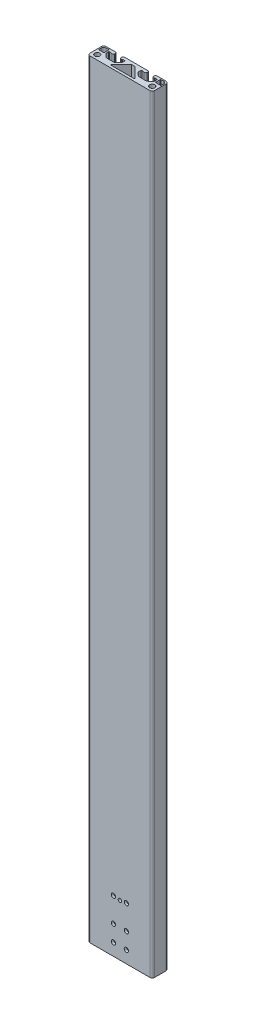
SolidWorks part; units mm, degrees
ref_plane "Front Plane" through (0, 0, 0) normal (0, 0, 1) x (1, 0, 0)
ref_plane "Top Plane" through (0, 0, 0) normal (0, 1, 0) x (1, 0, 0)
ref_plane "Right Plane" through (0, 0, 0) normal (1, 0, 0) x (0, 0, -1)
ref_plane "Plane1" through (0, 0, 0) normal (0, -1, 0) x (1, 0, 0)
sketch "Sketch1" plane through (0, 0, 0) normal (0, -1, 0) x (1, 0, 0)
  line L0 (7.45, -18.5) -> (4.3, -18.5)
  line L1 (1.5, -15.7) -> (1.5, -12.75)
  line L2 (2.25, -12) -> (7.45, -12)
  line L3 (8.2, -12.75) -> (8.2, -17.75)
  line L4 (54.5464, -3.8536) -> (41.9, -16.5)
  line L5 (41.9, -16.5) -> (38.1, -16.5)
  line L6 (38.1, -16.5) -> (25.4536, -3.8536)
  line L7 (25.8071, -3) -> (54.1929, -3)
  line L8 (71.8, -17.75) -> (71.8, -12.75)
  line L9 (72.55, -12) -> (77.75, -12)
  line L10 (78.5, -12.75) -> (78.5, -15.7)
  line L11 (75.7, -18.5) -> (72.55, -18.5)
  line L12 (77, 0) -> (3, 0)
  line L13 (0, -3) -> (0, -17)
  line L14 (3, -20) -> (14.5, -20)
  line L15 (16, -18.5) -> (16, -17.5)
  line L16 (14.5, -16) -> (13.2, -16)
  line L17 (13.2, -16) -> (13.2, -16.5)
  line L18 (13.2, -16.5) -> (10.75, -16.5)
  line L19 (10, -15.75) -> (10, -12.8107)
  line L20 (10.2197, -12.2803) -> (13.1088, -9.3912)
  line L21 (16.4675, -8) -> (23.5325, -8)
  line L22 (26.8912, -9.3912) -> (29.7803, -12.2803)
  line L23 (30, -12.8107) -> (30, -15.75)
  line L24 (29.25, -16.5) -> (26.8, -16.5)
  line L25 (26.8, -16.5) -> (26.8, -16)
  line L26 (26.8, -16) -> (25.5, -16)
  line L27 (24, -17.5) -> (24, -18.5)
  line L28 (25.5, -20) -> (54.5, -20)
  line L29 (56, -18.5) -> (56, -17.5)
  line L30 (54.5, -16) -> (53.2, -16)
  line L31 (53.2, -16) -> (53.2, -16.5)
  line L32 (53.2, -16.5) -> (50.75, -16.5)
  line L33 (50, -15.75) -> (50, -12.8107)
  line L34 (50.2197, -12.2803) -> (53.1088, -9.3912)
  line L35 (56.4675, -8) -> (63.5325, -8)
  line L36 (66.8912, -9.3912) -> (69.7803, -12.2803)
  line L37 (70, -12.8107) -> (70, -15.75)
  line L38 (69.25, -16.5) -> (66.8, -16.5)
  line L39 (66.8, -16.5) -> (66.8, -16)
  line L40 (66.8, -16) -> (65.5, -16)
  line L41 (64, -17.5) -> (64, -18.5)
  line L42 (65.5, -20) -> (77, -20)
  line L43 (80, -17) -> (80, -3)
  circle A0 centre (6, -6) radius 3.175
  arc A1 (8.2, -17.75) -> (7.45, -18.5) centre (7.45, -17.75) cw
  arc A2 (4.3, -18.5) -> (1.5, -15.7) centre (4.3, -15.7) cw
  arc A3 (1.5, -12.75) -> (2.25, -12) centre (2.25, -12.75) cw
  arc A4 (7.45, -12) -> (8.2, -12.75) centre (7.45, -12.75) cw
  arc A5 (25.4536, -3.8536) -> (25.8071, -3) centre (25.8071, -3.5) cw
  arc A6 (54.1929, -3) -> (54.5464, -3.8536) centre (54.1929, -3.5) cw
  circle A7 centre (74, -6) radius 3.175
  arc A8 (72.55, -18.5) -> (71.8, -17.75) centre (72.55, -17.75) cw
  arc A9 (71.8, -12.75) -> (72.55, -12) centre (72.55, -12.75) cw
  arc A10 (77.75, -12) -> (78.5, -12.75) centre (77.75, -12.75) cw
  arc A11 (78.5, -15.7) -> (75.7, -18.5) centre (75.7, -15.7) cw
  arc A12 (80, -3) -> (77, 0) centre (77, -3) ccw
  arc A13 (3, 0) -> (0, -3) centre (3, -3) ccw
  arc A14 (0, -17) -> (3, -20) centre (3, -17) ccw
  arc A15 (14.5, -20) -> (16, -18.5) centre (14.5, -18.5) ccw
  arc A16 (16, -17.5) -> (14.5, -16) centre (14.5, -17.5) ccw
  arc A17 (10.75, -16.5) -> (10, -15.75) centre (10.75, -15.75) cw
  arc A18 (10, -12.8107) -> (10.2197, -12.2803) centre (10.75, -12.8107) cw
  arc A19 (13.1088, -9.3912) -> (16.4675, -8) centre (16.4675, -12.75) cw
  arc A20 (23.5325, -8) -> (26.8912, -9.3912) centre (23.5325, -12.75) cw
  arc A21 (29.7803, -12.2803) -> (30, -12.8107) centre (29.25, -12.8107) cw
  arc A22 (30, -15.75) -> (29.25, -16.5) centre (29.25, -15.75) cw
  arc A23 (25.5, -16) -> (24, -17.5) centre (25.5, -17.5) ccw
  arc A24 (24, -18.5) -> (25.5, -20) centre (25.5, -18.5) ccw
  arc A25 (54.5, -20) -> (56, -18.5) centre (54.5, -18.5) ccw
  arc A26 (56, -17.5) -> (54.5, -16) centre (54.5, -17.5) ccw
  arc A27 (50.75, -16.5) -> (50, -15.75) centre (50.75, -15.75) cw
  arc A28 (50, -12.8107) -> (50.2197, -12.2803) centre (50.75, -12.8107) cw
  arc A29 (53.1088, -9.3912) -> (56.4675, -8) centre (56.4675, -12.75) cw
  arc A30 (63.5325, -8) -> (66.8912, -9.3912) centre (63.5325, -12.75) cw
  arc A31 (69.7803, -12.2803) -> (70, -12.8107) centre (69.25, -12.8107) cw
  arc A32 (70, -15.75) -> (69.25, -16.5) centre (69.25, -15.75) cw
  arc A33 (65.5, -16) -> (64, -17.5) centre (65.5, -17.5) ccw
  arc A34 (64, -18.5) -> (65.5, -20) centre (65.5, -18.5) ccw
  arc A35 (77, -20) -> (80, -17) centre (77, -17) ccw
extrude "Boss-Extrude1" add sketch "Sketch1" against normal blind 950
ref_plane "Mid-Plane" through (40, 0, 0) normal (1, 0, 0) x (0, 0, -1)
ref_plane "belt_mid" through (60, 0, 0) normal (1, 0, 0) x (0, 0, -1)
ref_plane "belt_mid_2" through (20, 0, 0) normal (-1, 0, 0) x (0, 0, 1)
hole_wizard "M5 Clearance Hole1" positions "Sketch2" profile "Sketch3" hole size "M5" standard "ANSI Metric"
sketch "Sketch2" plane through (0, 0, 0) normal (0, 0, 1) x (1, 0, 0)
  point P0 (48, 15)
  point P3 (48, 35)
  point P6 (48, 65)
  point P9 (32, 65)
  point P12 (32, 35)
  point P15 (32, 15)
sketch "Sketch3" plane through (48, 15, 0) normal (1, 0, 0) x (0, -1, 0)
  line L0 (0, 0) -> (0, 6.5923)
  line L1 (0, 6.5923) -> (2.65, 5)
  line L2 (2.65, 5) -> (2.65, 0)
  line L5 (2.65, 0) -> (0, 0)
  line L10 (0, 6.5923) -> (-2.65, 5) construction
  line L11 (0, -6.35) -> (0, 107.95) construction
  dimension "Hole Dia." = 5.3
  dimension "Hole Depth" = 5
  dimension "Drill Angle" = 118
hole_wizard "M5x0.8 Tapped Hole1" positions "Sketch4" profile "Sketch5" tap size "M5x0.8" standard "ANSI Metric" end condition through all
sketch "Sketch4" plane through (0, 0, -20) normal (0, 0, -1) x (-1, 0, 0)
  point P0 (-40, 64.001)
sketch "Sketch5" plane through (40, 64.001, -20) normal (1, 0, 0) x (0, 1, 0)
  line L0 (0, 0) -> (0, 20)
  line L1 (0, 20) -> (2.1, 20)
  line L2 (2.1, 20) -> (2.1, 0)
  line L5 (2.1, 0) -> (0, 0)
  line L11 (0, -6.35) -> (0, 107.95) construction
  dimension "Thru Tap Drill Dia." = 4.2
  dimension "Thru Tap Drill Depth" = 20
cosmetic thread "Hole Thread1" parameters "D2"=5
